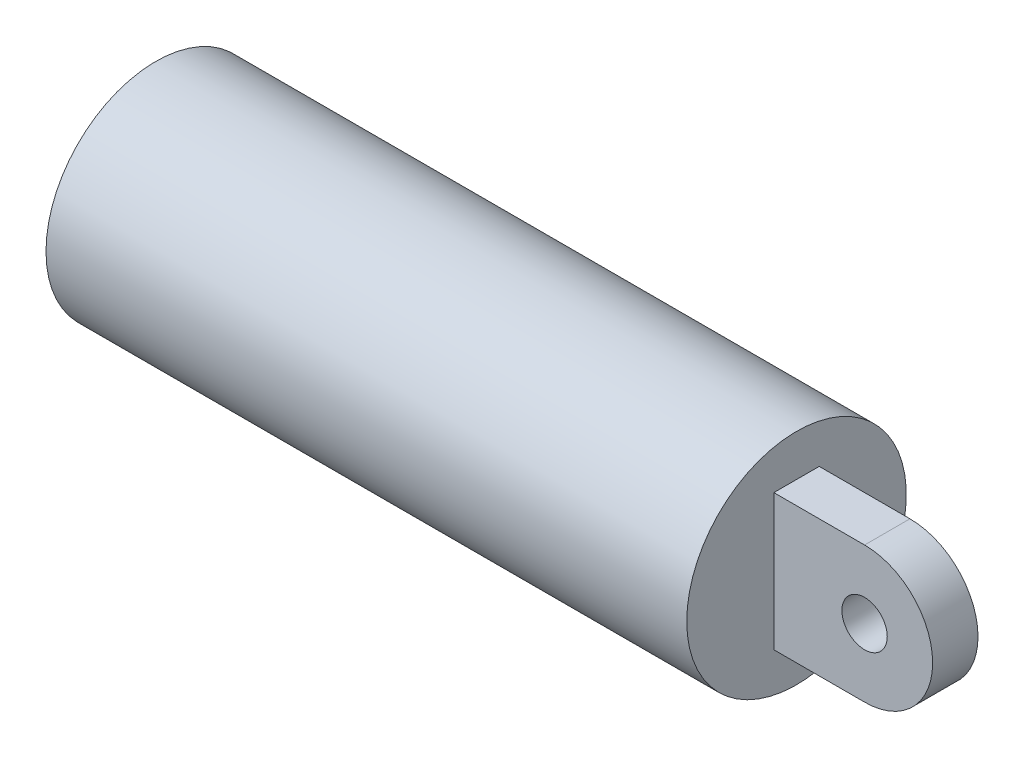
SolidWorks part; units mm, degrees
ref_plane "Front Plane" through (0, 0, 0) normal (0, 0, 1) x (1, 0, 0)
ref_plane "Top Plane" through (0, 0, 0) normal (0, 1, 0) x (1, 0, 0)
ref_plane "Right Plane" through (0, 0, 0) normal (1, 0, 0) x (0, 0, -1)
sketch "Sketch1" plane through (0, 0, 0) normal (0, 0, 1) x (1, 0, 0)
  line L5 (320, 39) -> (300, 39)
  line L6 (300, 39) -> (300, 9)
  line L7 (300, 9) -> (320, 9)
  circle A2 centre (320, 24) radius 5
  arc A3 (320, 9) -> (320, 39) centre (320, 24) ccw
  dimension "D1" = 10
  dimension "D2" = 30
  dimension "D3" = 20
extrude "Boss-Extrude1" add sketch "Sketch1" along normal mid plane 10
sketch "Sketch4" plane through (0, 0, 0) normal (0, 0, 1) x (1, 0, 0)
  line L0 (300, 39) -> (300, 48.1985)
  line L1 (300, 39) -> (300, 9) construction
  line L2 (320, 39) -> (300, 39) construction
  line L3 (300, 48.1985) -> (158.7644, 48.1985)
  line L4 (158.7644, 48.1985) -> (158.7644, 39)
  line L5 (158.7644, 39) -> (289.0254, 39)
  line L6 (289.0254, 39) -> (289.0254, 24)
  line L7 (289.0254, 24) -> (300, 24)
  line L8 (300, 24) -> (300, 39)
revolve "Revolve2" add sketch "Sketch4" angle 360 about L7
